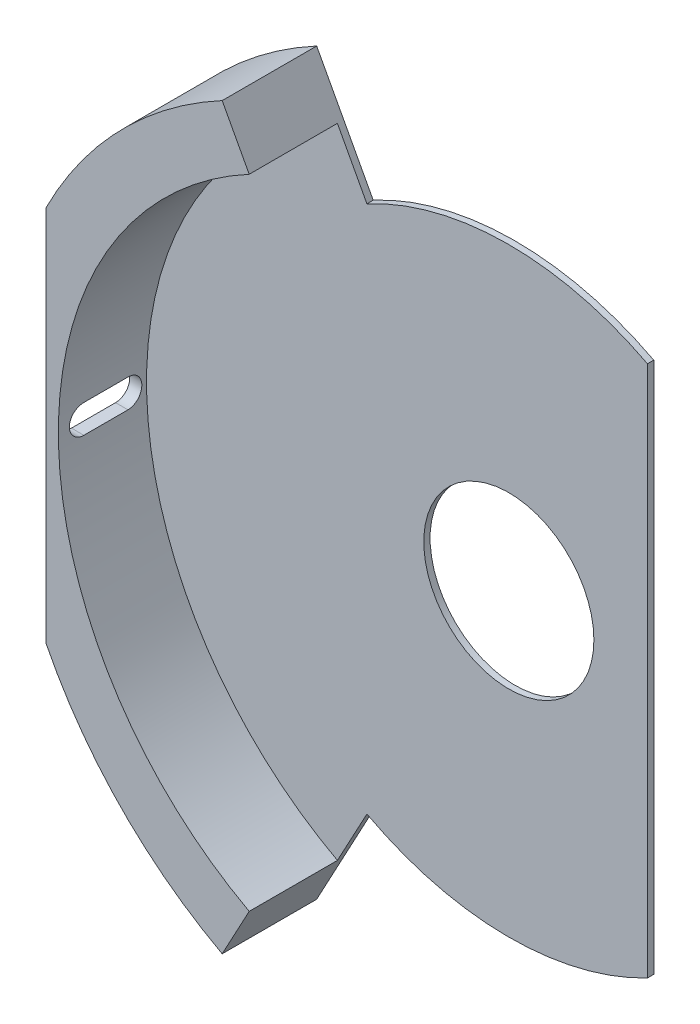
SolidWorks part; units mm, degrees
ref_plane "Front Plane" through (0, 0, 0) normal (0, 0, 1) x (1, 0, 0)
ref_plane "Top Plane" through (0, 0, 0) normal (0, 1, 0) x (1, 0, 0)
ref_plane "Right Plane" through (0, 0, 0) normal (1, 0, 0) x (0, 0, -1)
sketch "Sketch1" plane through (0, 0, 0) normal (0, 0, 1) x (1, 0, 0)
  line L1 (-24.9265, 30.0943) -> (37.4943, 30.0943)
  line L2 (-24.9265, 30.0943) -> (-24.9265, -29.9057)
  line L3 (-24.9265, -29.9057) -> (37.4943, -29.9057)
  line L4 (37.4943, 30.0943) -> (37.4943, -29.9057)
  line L5 (-23.9265, -4.499) -> (-23.9265, 4.6875) construction
  circle A0 centre (15.4943, 0.0943) radius 13.5
  circle A2 centre (15.4943, 0.0943) radius 13.1445 construction
  point P7 (37.4943, 0.0943)
  dimension "D1" = 27
  dimension "D2" = 60
  dimension "D3" = 22
  dimension "D4" = 1
extrude "Boss-Extrude1" add sketch "Sketch1" along normal blind 1 contours A0 L4 L1 L2 L3
sketch "Sketch2" plane through (0, 0, 1) normal (0, 0, 1) x (1, 0, 0)
  line L1 (-24.9265, -29.9057) -> (29.0043, -29.9057)
  line L2 (-24.9265, -29.9057) -> (-24.9265, -25.3057)
  line L3 (-24.9265, 30.0943) -> (37.4943, 30.0943) construction
  line L4 (29.0043, -29.9057) -> (29.0043, -25.3057)
  line L5 (-24.9265, 30.0943) -> (-24.9265, -29.9057) construction
  line L6 (29.0043, 30.0943) -> (-24.9265, 30.0943)
  line L7 (29.0043, 30.0943) -> (29.0043, 25.4943)
  line L8 (32.0043, 22.3193) -> (32.0043, -22.1307) construction
  line L9 (-24.9265, 30.0943) -> (-24.9265, 25.4943)
  line L10 (29.0043, -29.9057) -> (-24.9265, -29.9057)
  line L11 (-28.3207, 25.4943) -> (28.8293, 25.4943) construction
  line L12 (28.8293, -25.3057) -> (-28.3207, -25.3057) construction
  line L13 (29.0043, -29.9057) -> (29.0043, -25.3057)
  line L14 (29.0043, -25.3057) -> (-24.9265, -25.3057)
  line L15 (-24.9265, -29.9057) -> (-24.9265, -25.3057)
  line L16 (29.0043, 30.0943) -> (-24.9265, 30.0943)
  line L17 (29.0043, 30.0943) -> (29.0043, 25.4943)
  line L18 (29.0043, 25.4943) -> (-24.9265, 25.4943)
  line L19 (-24.9265, 30.0943) -> (-24.9265, 25.4943)
  line L28 (29.0043, 30.0943) -> (22.0043, 30.0943)
  line L29 (29.0043, 30.0943) -> (29.0043, 25.4943)
  line L30 (29.0043, 25.4943) -> (22.0043, 25.4943)
  line L31 (22.0043, 30.0943) -> (22.0043, 25.4943)
  line L33 (29.0043, -29.9057) -> (22.0043, -29.9057)
  line L34 (29.0043, -29.9057) -> (29.0043, -25.3057)
  line L35 (29.0043, -25.3057) -> (22.0043, -25.3057)
  line L36 (22.0043, -29.9057) -> (22.0043, -25.3057)
  line L38 (-24.9265, -29.9057) -> (-17.9265, -29.9057)
  line L39 (-24.9265, -29.9057) -> (-24.9265, -25.3057)
  line L40 (-24.9265, -25.3057) -> (-17.9265, -25.3057)
  line L41 (-17.9265, -29.9057) -> (-17.9265, -25.3057)
  line L42 (-24.9265, 30.0943) -> (-17.9265, 30.0943)
  line L43 (-24.9265, 30.0943) -> (-24.9265, 25.4943)
  line L44 (-24.9265, 25.4943) -> (-17.9265, 25.4943)
  line L45 (-17.9265, 30.0943) -> (-17.9265, 25.4943)
  dimension "D1" = 7
  dimension "D2" = 7
  dimension "D3" = 3
extrude "Boss-Extrude2" add sketch "Sketch2" against normal blind 7 from surface at -1 starting at face at (28.9943, 0.0943, 0)
sketch "Sketch3" plane through (0, 0, 1) normal (0, 0, 1) x (1, 0, 0)
  line L0 (37.4943, -53.0306) -> (37.4943, 53.2191)
  line L1 (37.4943, 30.0943) -> (37.4943, -29.9057) construction
  line L2 (-16.0032, -58.5465) -> (-11.714, -50.561)
  line L3 (-24.9265, 30.0943) -> (-43.9265, 30.0943)
  line L4 (-24.9265, 30.0943) -> (-24.9265, -29.9057)
  line L5 (-24.9265, -29.9057) -> (-43.9265, -29.9057)
  line L6 (-43.9265, 30.0943) -> (-43.9265, -29.9057)
  line L7 (-16.0032, 58.735) -> (-11.714, 50.7495)
  circle A0 centre (15.4943, 0.0943) radius 57.5
  arc A1 (-43.9265, -29.9057) -> (-16.0032, -58.5465) centre (15.4943, 0.0943) ccw
  arc A2 (-43.9265, 30.0943) -> (-16.0032, 58.735) centre (15.4943, 0.0943) cw
  arc A3 (-11.714, 50.7495) -> (-33.5592, 30.0943) centre (15.4943, 0.0943) ccw
  arc A4 (-11.714, -50.561) -> (-33.5592, -29.9057) centre (15.4943, 0.0943) cw
  dimension "D1" = 115
  dimension "D3" = 40
  dimension "D2" = 19
  dimension "D4" = 40
extrude "Boss-Extrude3" add sketch "Sketch3" along normal blind 14 separate body contours A2 L3 A0 L7 | A0 L3 L6 L5 | L5 A1 L2 A0
sketch "Sketch4" plane through (0, 0, 1) normal (0, 0, 1) x (1, 0, 0)
  line L0 (37.4943, -53.0306) -> (37.4943, 53.2191)
  line L1 (-24.9265, 30.0943) -> (-43.9265, 30.0943)
  line L2 (-24.9265, 30.0943) -> (-24.9265, -29.9057)
  line L3 (-24.9265, -29.9057) -> (-43.9265, -29.9057)
  line L4 (-43.9265, 30.0943) -> (-43.9265, -29.9057)
  line L5 (37.4943, 30.0943) -> (37.4943, -29.9057) construction
  line L6 (-11.714, -50.561) -> (-16.0032, -58.5465)
  line L7 (-11.714, 50.7495) -> (-16.0032, 58.735)
  line L8 (-43.9265, -29.9057) -> (-43.9265, 30.0943)
  line L9 (-11.714, -50.561) -> (-4.7577, -37.6101)
  line L10 (-11.714, 50.7495) -> (-4.0722, 36.5223)
  circle A0 centre (15.4943, 0.0943) radius 57.5
  circle A1 centre (15.4943, 0.0943) radius 13.5 construction
  arc A2 (-16.0032, -58.5465) -> (-43.9265, -29.9057) centre (15.4943, 0.0943) cw
  arc A3 (-16.0032, 58.735) -> (-43.9265, 30.0943) centre (15.4943, 0.0943) ccw
  arc A4 (-16.0032, 58.735) -> (-43.9265, 30.0943) centre (15.4943, 0.0943) ccw construction
  arc A5 (-11.714, 50.7495) -> (-11.714, -50.561) centre (15.4943, 0.0943) cw
  arc A6 (-11.714, 50.7495) -> (-11.714, -50.561) centre (15.4943, 0.0943) ccw construction
  arc A7 (-7.0307, -41.8418) -> (-7.0307, 42.0304) centre (15.4943, 0.0943) ccw
  line M7 (37.4943, 30.0943) -> (-24.9265, 30.0943)
  line M8 (-24.9265, 30.0943) -> (-24.9265, -29.9057)
  line M9 (-24.9265, -29.9057) -> (37.4943, -29.9057)
  dimension "D1" = 115
extrude "Boss-Extrude4" add sketch "Sketch4" against normal up to surface (1 mm away) contours L3 A0 L0 M9 | L1 A0 L4 L3 M8 | L0 A0 L1 M7 | A0 L4 L3 | A0 L1 L4 | A2 L6 A0 L3 | L7 A3 L1 A0
sketch "Sketch5" plane through (-43.9265, 0, 0) normal (-1, 0, 0) x (0, 0, 1)
  line L0 (4, 0) -> (11, 0) construction
  line L1 (4, 2.25) -> (11, 2.25)
  line L2 (4, -2.25) -> (11, -2.25)
  line L3 (0, -29.9057) -> (0, 30.0943) construction
  arc A0 (4, 2.25) -> (4, -2.25) centre (4, 0) ccw
  arc A1 (11, -2.25) -> (11, 2.25) centre (11, 0) ccw
  point P3 (7.5, 0)
  dimension "D1" = 2.25
  dimension "D2" = 7
  dimension "D3" = 4
extrude "Cut-Extrude1" cut sketch "Sketch5" against normal up to next
